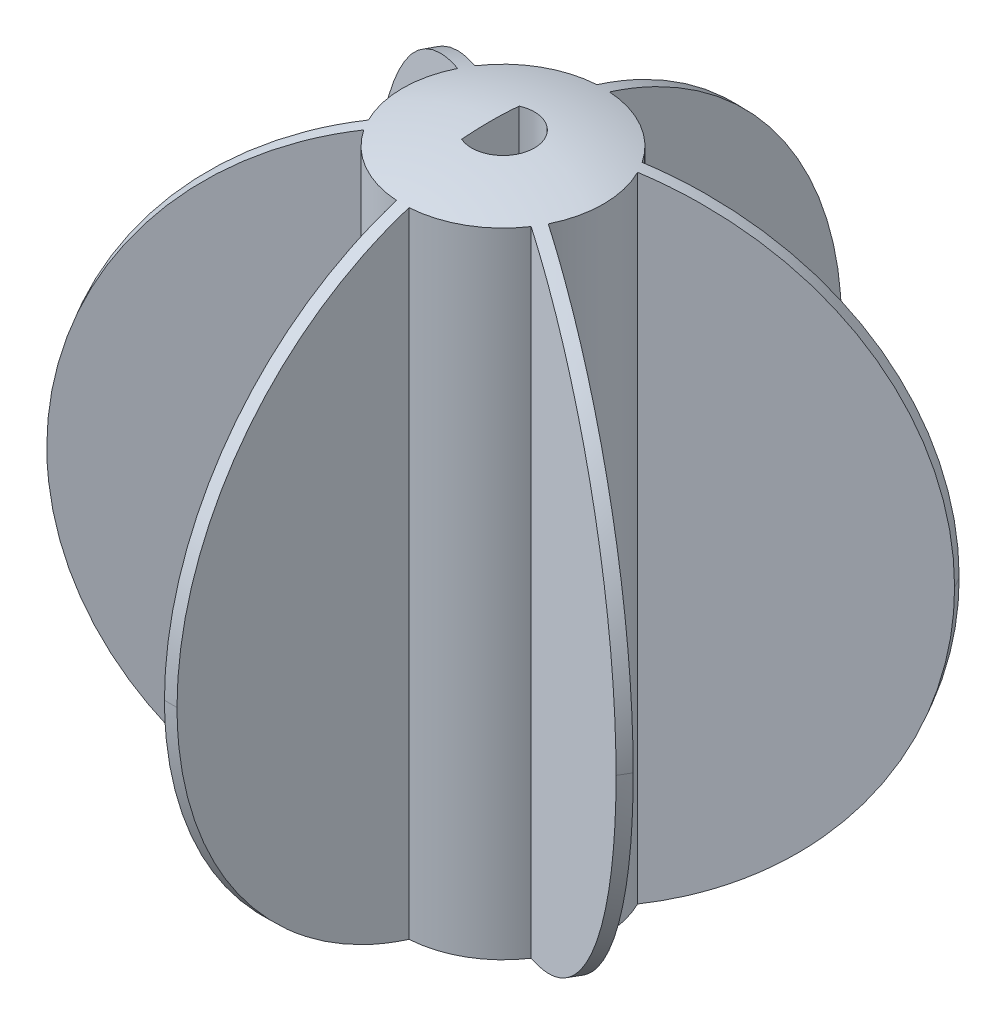
SolidWorks part; units mm, degrees
ref_plane "Front Plane" through (0, 0, 0) normal (0, 0, 1) x (1, 0, 0)
ref_plane "Top Plane" through (0, 0, 0) normal (0, 1, 0) x (1, 0, 0)
ref_plane "Right Plane" through (0, 0, 0) normal (1, 0, 0) x (0, 0, -1)
sketch "Sketch1" plane through (0, 0, 0) normal (0, 1, 0) x (1, 0, 0)
  line L0 (-13.4, -44.6711) -> (-13.4, 39.4029)
  line L1 (-49.8051, -23.6526) -> (23.0051, 18.3844)
  line L2 (-49.8051, 18.3844) -> (23.0051, -23.6526)
  line L3 (-12.6063, -44.6636) -> (-12.6063, 39.3954)
  line L4 (-49.4018, -24.3363) -> (23.3955, 17.6933)
  line L5 (-50.1955, 17.6933) -> (22.6017, -24.3363)
  line L6 (-14.1938, -44.6636) -> (-14.1938, 39.3954)
  line L7 (-50.1955, -22.9614) -> (22.6017, 19.0681)
  line L8 (-49.4018, 19.0681) -> (23.3955, -22.9614)
  line L9 (-40.8202, 14.1135) -> (43260.45, -24985.8865) construction
  line L10 (-41.2171, 13.4261) -> (43260.0531, -24986.5739) construction
  line L11 (-41.614, 12.7387) -> (43259.6562, -24987.2613) construction
  line L12 (-37.5885, -15.6828) -> (43263.6817, 24984.3172) construction
  line L13 (-37.1917, -16.3702) -> (43264.0785, 24983.6298) construction
  line L14 (-36.7948, -17.0576) -> (43264.4754, 24982.9424) construction
  line L15 (-14.1938, -1002.6341) -> (-14.1938, 48997.3659) construction
  line L16 (-13.4, -1002.6341) -> (-13.4, 48997.3659) construction
  line L17 (-12.6063, -1002.6341) -> (-12.6063, 48997.3659) construction
  circle A0 centre (-13.4, -2.6341) radius 12.7
  circle A1 centre (-13.4, -2.6341) radius 42.037
  dimension "D1" = 25.4
  dimension "D6" = 84.074
  dimension "D2" = 60
  dimension "D3" = 60
  dimension "D4" = 0.7937
  dimension "D5" = 0.7937
extrude "Boss-Extrude1" add sketch "Sketch1" along normal blind 84.074 contours L8 A0 L4 | L7 A0 L3 | L6 A0 L8 | L5 A0 L7 | L4 A0 L6 | L3 A0 L5 | L3 A0 L0 L7 | L0 A0 L6 L8 | L8 A0 L2 L6 | L2 A0 L5 L7 | L1 A0 L7 L3 | L4 A0 L1 L8 | L0 A0 L3 L5 | L6 A0 L0 L4 | L7 A0 L1 L5 | L1 A0 L4 L6 | L5 A0 L2 L3 | L2 A0 L8 L4 | L7 L8 L3 | L8 L0 L1 | L7 L2 L0 | L8 L6 L7 | L7 L5 L6 | L6 L1 L2 | L1 L5 L0 | L0 L4 L2 | L2 L3 L1 | L8 L3 L4 | L4 L5 L3 | L6 L4 L5 | L5 A1 L2 A0 | L2 A1 L8 A0 | L0 A1 L3 A0 | L6 A1 L0 A0 | L1 A1 L4 A0 | L7 A1 L1 A0 | L2 A1 L5 A0 | L8 A1 L2 A0 | L0 A1 L6 A0 | L3 A1 L0 A0 | L1 A1 L7 A0 | L4 A1 L1 A0
ref_plane "Plane1" through (-4.4906, 0, 7.7779) normal (-0.5, 0, 0.866) x (0.866, 0, 0.5)
sketch "Sketch5" plane through (-4.4906, 0, 7.7779) normal (-0.5, 0, 0.866) x (0.866, 0, 0.5)
  line L0 (-10.2877, 84.074) -> (-10.2877, 0) construction
  line L1 (-4.6375, 84.074) -> (-15.9379, 84.074) construction
  line L2 (-15.9379, 0) -> (-4.6375, 0) construction
  line L3 (-10.2877, 0) -> (31.7418, 0) construction
  line L4 (31.7418, 0) -> (31.7418, 84.074) construction
  line L5 (31.7418, 84.074) -> (-10.2877, 84.074) construction
  line L6 (-10.2877, 84.074) -> (-10.2877, 96.808)
  line L7 (-10.2877, 96.808) -> (48.4873, 96.808)
  line L8 (48.4873, 96.808) -> (48.4873, -11.7874)
  line L9 (48.4873, -11.7874) -> (-10.2877, -11.7874)
  line L10 (-10.2877, -11.7874) -> (-10.2877, 0)
  arc A0 (-10.2877, 84.074) -> (31.7418, 42.037) centre (-10.2877, 42.0445) cw
  arc A1 (31.7418, 42.037) -> (-10.2877, 0) centre (-10.3027, 42.0445) cw
revolve "Cut-Revolve6" cut sketch "Sketch5" angle 360 about L0
sketch "Sketch6" plane through (0, 0, 0) normal (0, 1, 0) x (1, 0, 0)
  circle A0 centre (-13.4, -2.6341) radius 3.9688
  dimension "D1" = 7.9375
extrude "Boss-Extrude3" add sketch "Sketch6" against normal blind 2.3813 and the other way up to surface
sketch "Sketch7" plane through (0, 0, 0) normal (0, 1, 0) x (1, 0, 0)
  line L0 (-14.9875, 1.0033) -> (-14.9875, -6.2715)
  line L1 (-14.9875, -2.6341) -> (-9.4313, -2.6341)
  circle A0 centre (-13.4, -2.6341) radius 3.9688
  arc A1 (-2.8199, 4.3909) -> (-12.6063, 10.0411) centre (-13.4, -2.6341) ccw construction
  dimension "D1" = 7.9375
  dimension "D2" = 5.5562
extrude "Cut-Extrude2" cut sketch "Sketch7" along normal blind 127 from offset 12.7 contours L1 A0 L0 | L0 A0 L1
